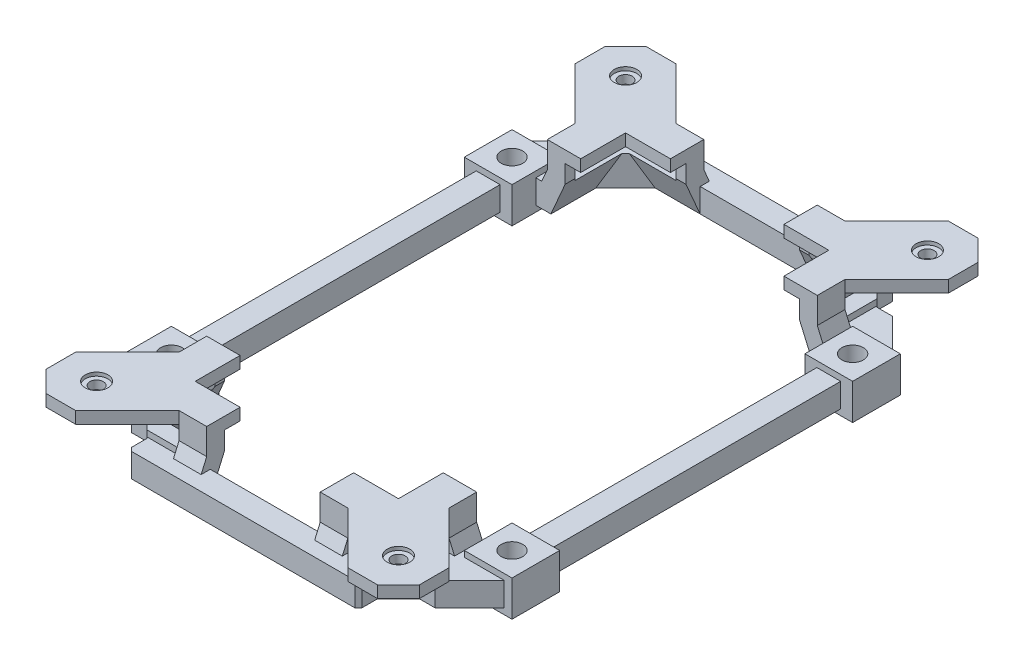
SolidWorks part; units mm, degrees
ref_plane "Front Plane" through (0, 0, 0) normal (0, 0, 1) x (1, 0, 0)
ref_plane "Top Plane" through (0, 0, 0) normal (0, 1, 0) x (1, 0, 0)
ref_plane "Right Plane" through (0, 0, 0) normal (1, 0, 0) x (0, 0, -1)
sketch "Sketch1" plane through (0, 0, 0) normal (0, 1, 0) x (1, 0, 0)
  line L0 (-53.15, 0) -> (-61.15, 0)
  line L1 (-61.15, 0) -> (-61.15, -49.15)
  line L2 (-61.15, -49.15) -> (-65.15, -49.15)
  line L3 (-65.15, -49.15) -> (-65.15, -65.15)
  line L4 (-65.15, -65.15) -> (-62.5102, -65.15)
  line L6 (-62.5102, -65.15) -> (-37.4602, -90.2)
  line L17 (-53.15, 0) -> (-53.15, -49.15)
  line L18 (-53.15, -49.15) -> (-49.15, -49.15)
  line L19 (-49.15, -49.15) -> (-49.15, -57.15)
  line L24 (-53.15, 0) -> (0, 0) construction
  line L25 (0, 0) -> (0, -92.25) construction
  line L26 (-39.3, -57.15) -> (-38.1, -57.15) construction
  line L27 (-38.1, 0) -> (-38.1, -76.2) construction
  line L28 (-65.15, -57.15) -> (-49.15, -57.15) construction
  line L29 (-38.1, -76.2) -> (0, -76.2) construction
  line L37 (-38.1, -76.2) -> (-39.3, -77.4) construction
  line L38 (-39.3, -77.4) -> (-39.3, -57.15) construction
  line L39 (-49.15, -57.15) -> (-39.3, -57.15)
  line L41 (-39.3, -77.4) -> (-19.05, -77.4) construction
  line L42 (-19.05, -77.4) -> (-19.05, -82.2)
  line L44 (-37.4602, -90.2) -> (0, -90.2)
  line L45 (0, -90.2) -> (0, -82.2)
  line L46 (0, -82.2) -> (-19.05, -82.2)
  line L47 (-39.3, -57.15) -> (-39.3, -74.6464)
  line L49 (-36.5464, -77.4) -> (-19.05, -77.4)
  line L50 (-19.05, -77.4) -> (-19.05, -76.2) construction
  line L51 (-39.3, -74.6464) -> (-36.5464, -77.4)
  line L52 (-39.3, -74.6464) -> (-49.15, -64.7964) construction
  line L53 (-49.15, -64.7964) -> (-49.15, -57.15) construction
  point P37 (-57.15, 0)
  dimension "D1" = 8
  dimension "D2" = 16
  dimension "D4" = 57.15
  dimension "D5" = 57.15
  dimension "D6" = 76.2
  dimension "D7" = 38.1
  dimension "D8" = 45
  dimension "D10" = 6
  dimension "D3" = 1.2
  dimension "D11" = 135
  dimension "D12" = 0.25
  dimension "D13" = 7.75
extrude "Boss-Extrude1" add sketch "Sketch1" along normal blind 8
sketch "Sketch2" plane through (0, 0, 0) normal (0, -1, 0) x (1, 0, 0)
  line L0 (-49.15, 57.15) -> (-49.15, 49.15) construction
  line L1 (-65.15, 49.15) -> (-65.15, 65.15) construction
  line L2 (-49.15, 57.15) -> (-49.15, 49.15)
  line L3 (-65.15, 49.15) -> (-65.15, 65.15)
  line L5 (-65.15, 49.15) -> (-49.15, 49.15)
  line L6 (-65.15, 65.15) -> (-49.15, 65.15)
  line L7 (-49.15, 65.15) -> (-49.15, 57.15)
extrude "Boss-Extrude2" add sketch "Sketch2" along normal blind 2
sketch "Sketch3" plane through (0, 8, 0) normal (0, 1, 0) x (1, 0, 0)
  line L4 (-39.3, -57.15) -> (-45.3, -57.15)
  line L6 (-45.3, -57.15) -> (-45.3, -77.1317)
  line L9 (-19.05, -83.4) -> (-19.05, -77.4)
  line L10 (-45.3, -77.1317) -> (-39.0317, -83.4)
  line L11 (-39.0317, -83.4) -> (-19.05, -83.4)
  line L12 (-62.5102, -65.15) -> (-37.4602, -90.2) construction
  line L13 (-39.3, -57.15) -> (-39.3, -74.6464)
  line L14 (-39.3, -74.6464) -> (-36.5464, -77.4)
  line L15 (-36.5464, -77.4) -> (-19.05, -77.4)
  line L16 (-19.05, -77.4) -> (-36.5464, -77.4) construction
  line L17 (-39.3, -74.6464) -> (-39.3, -57.15) construction
  line L18 (-39.3, -57.15) -> (-49.15, -57.15) construction
  line L19 (-19.05, -82.2) -> (-19.05, -77.4) construction
  line L20 (-39.3, -74.6464) -> (-43.5426, -78.8891) construction
  line L21 (-39.3, -74.6464) -> (-45.3, -74.6464) construction
  dimension "D1" = 6
extrude "Boss-Extrude3" add sketch "Sketch3" along normal blind 9.05
sketch "Sketch4" plane through (0, 17.05, 0) normal (0, 1, 0) x (1, 0, 0)
  line L0 (-45.3, -57.15) -> (-34.1, -57.15)
  line L1 (-34.1, -57.15) -> (-34.1, -72.2)
  line L2 (-34.1, -72.2) -> (-19.05, -72.2)
  line L3 (-19.05, -72.2) -> (-19.05, -83.4)
  line L4 (-19.05, -83.4) -> (-28.3294, -83.4)
  line L5 (-39.0317, -83.4) -> (-19.05, -83.4) construction
  line L6 (-28.3294, -83.4) -> (-45.6806, -100.7511)
  line L7 (-45.6806, -100.7511) -> (-55.6217, -100.7511)
  line L8 (-55.6217, -100.7511) -> (-62.6511, -93.7217)
  line L9 (-62.6511, -93.7217) -> (-62.6511, -83.7806)
  line L10 (-62.6511, -83.7806) -> (-45.3, -66.4294)
  line L11 (-45.3, -66.4294) -> (-45.3, -57.15)
  line L12 (-50.6511, -88.7511) -> (-59.1364, -97.2364) construction
  line L13 (-50.6511, -88.7511) -> (-62.6511, -88.7511) construction
  line L14 (-49.0602, -87.1602) -> (-42.1659, -80.2659) construction
  line L15 (-45.3, -77.1317) -> (-39.0317, -83.4) construction
  line L16 (-60.7274, -81.8569) -> (-43.7569, -98.8274) construction
  line L20 (-50.6511, -88.7511) -> (-42.1659, -80.2659) construction
  line L22 (-45.3, -66.4294) -> (-39.3, -60.4294) construction
  line L23 (-39.3, -74.6464) -> (-39.3, -57.15) construction
  circle A0 centre (-50.6511, -88.7511) radius 2.25
  circle A1 centre (-50.6511, -88.7511) radius 10 construction
  dimension "D4" = 4.5
  dimension "D7" = 20
  dimension "D1" = 11.2
  dimension "D2" = 135
  dimension "D3" = 135
  dimension "D5" = 12
extrude "Boss-Extrude4" add sketch "Sketch4" along normal blind 4
sketch "Sketch5" plane through (-61.2159, 0, 61.2159) normal (-0.7071, 0, 0.7071) x (0.7071, 0, 0.7071)
  line L1 (14.9408, 17.05) -> (38.9408, 17.05)
  line L2 (14.9408, 17.05) -> (14.9408, 10.05)
  line L3 (14.9408, 10.05) -> (38.9408, 10.05)
  line L4 (38.9408, 17.05) -> (38.9408, 10.05)
  line L6 (22.5084, 17.05) -> (31.3731, 17.05) construction
  line L7 (14.9408, 21.05) -> (14.9408, 17.05) construction
  line L9 (38.9408, 21.05) -> (38.9408, 17.05) construction
  dimension "D1" = 7
extrude "Cut-Extrude1" cut sketch "Sketch5" against normal up to next and the other way through all
sketch "Sketch7" plane through (0, 0, 0) normal (0, -1, 0) x (1, 0, 0)
  line L0 (-37.4602, 90.2) -> (-34.1464, 82.2) construction
  line L1 (-31.8865, 84.46) -> (-37.4059, 78.9405) construction
  line L2 (-34.1464, 82.2) -> (0, 82.2) construction
  line L3 (0, 82.2) -> (-19.05, 82.2) construction
  line L4 (-62.5102, 65.15) -> (-37.4602, 90.2) construction
  line L5 (-37.4602, 90.2) -> (0, 90.2) construction
sketch "Sketch6" plane through (-19.05, 0, 0) normal (1, 0, 0) x (0, 0, -1)
  line L1 (-82.2, 0) -> (-77.4, 11.05)
  line L2 (-77.4, 17.05) -> (-77.4, 0) construction
  line L3 (-77.4, 11.05) -> (-77.4, 0)
  line L5 (-77.4, 17.05) -> (-72.2, 17.05) construction
  line L8 (-82.2, 0) -> (-77.4, 0)
  dimension "D1" = 6
extrude "Cut-Extrude2" cut sketch "Sketch6" against normal up to vertex (15.0964 mm away) up to point (-34.1464, 0, 82.2)
ref_plane "Plane1" through (19.05, 0, 19.05) normal (0.7071, 0, 0.7071) x (0.7071, 0, -0.7071)
mirror "Mirror1" about plane through (19.05, 0, 19.05) normal (0.7071, 0, 0.7071) of "Cut-Extrude2"
sketch "Sketch8" plane through (19.05, 0, 19.05) normal (0.7071, 0, 0.7071) x (0.7071, 0, -0.7071)
  line L8 (-82.2694, 0) -> (-82.2694, 10.05)
  line L9 (-82.2694, 10.05) -> (-78.8752, 10.05)
  line L10 (-78.8752, 10.05) -> (-78.8752, 0)
  line L11 (-78.8752, 0) -> (-82.2694, 0)
  line L12 (-78.8752, 0) -> (-78.8752, 10.05) construction
  line L13 (-79.1824, 10.05) -> (-78.8752, 10.05) construction
extrude "Cut-Extrude3" cut sketch "Sketch8" against normal up to surface and the other way up to surface up to face at (-41.0448, 7.0333, 63.3477) other way up to face at (-25.2477, 7.0333, 79.1448)
sketch "Sketch10" plane through (-19.05, 0, 0) normal (1, 0, 0) x (0, 0, -1)
  line L0 (-83.4, 12.2969) -> (-85.2665, 8)
  line L1 (-85.2665, 8) -> (-83.4, 8)
  line L2 (-83.4, 8) -> (-83.4, 12.2969)
  line L3 (-83.4, 21.05) -> (-83.4, 8) construction
  line L4 (-90.2, 8) -> (-82.2, 8) construction
  line L5 (-77.4, 11.05) -> (-82.2, 0) construction
  line L6 (-77.8344, 10.05) -> (-82.2, 0) construction
  dimension "D1" = 6
extrude "Boss-Extrude5" add sketch "Sketch10" against normal up to vertex (9.2794 mm away) up to point (-28.3294, 10.05, 83.4)
sketch "Sketch11" plane through (19.05, 0, 19.05) normal (0.7071, 0, 0.7071) x (0.7071, 0, -0.7071)
  line L0 (-86.5723, -12.3407) -> (-80.3245, 8)
  line L1 (-80.3245, 8) -> (-86.5723, 8)
  line L2 (-86.5723, 8) -> (-86.5723, -12.3407)
  line L3 (-86.5723, 10.05) -> (-86.5723, 8) construction
  line L4 (-80.3245, 8) -> (-79.0046, 8) construction
  line L5 (-79.0046, 12.2969) -> (-80.3245, 8) construction
extrude "Cut-Extrude4" [suppressed] cut sketch "Sketch11" along normal through all
mirror "Mirror2" about plane through (19.05, 0, 19.05) normal (0.7071, 0, 0.7071) of "Cut-Extrude4", "Boss-Extrude5"
sketch "Sketch12" plane through (0, 8, 0) normal (0, 1, 0) x (1, 0, 0)
  line L0 (-65.15, -65.15) -> (-49.15, -49.15) construction
  circle A0 centre (-57.15, -57.15) radius 3.6
  point P7 (-57.15, -57.15)
  dimension "D1" = 7.2
extrude "Cut-Extrude5" cut sketch "Sketch12" against normal through all
mirror "Mirror3" about plane through (-53.15, 8, 0) normal (0, 0, 1) of bodies 112
mirror "Mirror4" about plane through (0, 8, -90.2) normal (-1, 0, 0) of bodies 113
sketch "Sketch13" plane through (0, 8, 0) normal (0, 1, 0) x (1, 0, 0)
  line L0 (-49.15, 49.15) -> (-53.15, 49.15) construction
  line L1 (-65.15, 65.15) -> (-49.15, 65.15)
  line L2 (-65.15, 65.15) -> (-65.15, 49.15)
  line L3 (-65.15, 49.15) -> (-49.15, 49.15)
  line L4 (-49.15, 65.15) -> (-49.15, 49.15)
  line L5 (-65.15, -49.15) -> (-49.15, -49.15)
  line L6 (-65.15, -49.15) -> (-65.15, -65.15)
  line L7 (-65.15, -65.15) -> (-49.15, -65.15)
  line L8 (-49.15, -49.15) -> (-49.15, -65.15)
  line L9 (49.15, -49.15) -> (65.15, -49.15)
  line L10 (49.15, -49.15) -> (49.15, -65.15)
  line L11 (49.15, -65.15) -> (65.15, -65.15)
  line L12 (65.15, -49.15) -> (65.15, -65.15)
  line L13 (49.15, 65.15) -> (65.15, 65.15)
  line L14 (49.15, 65.15) -> (49.15, 49.15)
  line L15 (49.15, 49.15) -> (65.15, 49.15)
  line L16 (65.15, 65.15) -> (65.15, 49.15)
  line L17 (-49.15, 57.15) -> (-49.15, 49.15) construction
  line L18 (-65.15, -65.15) -> (-62.5102, -65.15) construction
  line L19 (-65.15, -49.15) -> (-65.15, -65.15) construction
  line L20 (-49.15, -57.15) -> (-49.15, -49.15) construction
  line L21 (-49.15, -49.15) -> (-53.15, -49.15) construction
  line L22 (65.15, -65.15) -> (62.5102, -65.15) construction
  line L23 (61.15, -49.15) -> (65.15, -49.15) construction
  line L24 (65.15, -49.15) -> (65.15, -65.15) construction
  line L25 (49.15, -57.15) -> (49.15, -49.15) construction
  line L26 (65.15, 65.15) -> (62.5102, 65.15) construction
  line L27 (61.15, 49.15) -> (65.15, 49.15) construction
  line L28 (49.15, 57.15) -> (49.15, 49.15) construction
  line L29 (65.15, 49.15) -> (65.15, 65.15) construction
  line L30 (-65.15, 49.15) -> (-65.15, 65.15) construction
  line L31 (-65.15, 65.15) -> (-62.5102, 65.15) construction
  circle A0 centre (57.15, 57.15) radius 3.6 construction
  circle A1 centre (57.15, -57.15) radius 3.6 construction
  circle A2 centre (-57.15, -57.15) radius 3.6 construction
  circle A3 centre (-57.15, 57.15) radius 3.6 construction
  circle A4 centre (57.15, 57.15) radius 3.6
  circle A5 centre (57.15, -57.15) radius 3.6
  circle A6 centre (-57.15, -57.15) radius 3.6
  circle A7 centre (-57.15, 57.15) radius 3.6
extrude "Boss-Extrude6" add sketch "Sketch13" along normal blind 2
sketch "Sketch15" [suppressed] plane through (0, 0, 77.4) normal (0, 0, -1) x (-1, 0, 0)
  line L0 (39.3, 17.05) -> (-39.3, 17.05) construction
  line L1 (-37.4285, 0) -> (39.3, 17.05) construction
  line L2 (-37.5, 17.05) -> (-10.1111, 17.05)
  line L3 (-10.1111, 17.05) -> (-10.1111, 6.0703)
  line L4 (44.1, 0) -> (34.1464, 0) construction
  line L5 (-10.1111, 6.0703) -> (-35.6713, 0.3905)
  arc A0 (-39.3, 17.05) -> (-37.4285, 0) centre (39.3, 17.05) ccw construction
  arc A1 (-37.5, 17.05) -> (-35.6713, 0.3905) centre (39.3, 17.05) ccw
  dimension "D1" = 76.8
ref_plane "Plane2" [suppressed] through (39.1232, 9.05, 77.2232) normal (-0.7071, 0, 0.7071) x (0.7071, 0, 0.7071)
sketch "Sketch16" [suppressed] plane through (39.1232, 9.05, 77.2232) normal (-0.7071, 0, 0.7071) x (0.7071, 0, 0.7071)
  line L0 (-0.0384, 0.0028) -> (0, 0)
  line L1 (0.4004, 6.0709) -> (-0.1484, -1.5179) construction
  line L2 (0, 0) -> (-0.036, 0.036)
  line L3 (0, 0) -> (-2.9537, 0) construction
  ellipse E0 centre (-55.3286, 8) end of major axis (-55.3286, 86.6) minor radius 55.5786 (-1.0734, -9.05) -> (0.25, 8) ccw construction
  dimension "D1" = 45
sketch "Sketch17" [suppressed] plane through (-39.3, 0, 0) normal (1, 0, 0) x (0, 0, -1)
  line L0 (77.4, 17.05) -> (-77.4, 17.05) construction
  line L1 (-77.4, 17.05) -> (76.4582, 0) construction
  line L2 (-77.4, 17.05) -> (-77.4, 11.05) construction
  line L3 (77.4, 17.05) -> (77.4, 11.05) construction
  line L4 (72.2464, 0) -> (82.2, 0) construction
  line L5 (-72.2, 17.05) -> (-58.2, 17.05) construction
  line L6 (76.2, 17.05) -> (27.7638, 17.05)
  line L7 (27.7638, 17.05) -> (27.7638, 5.3961)
  line L8 (27.7638, 5.3961) -> (75.2655, 0.1322)
  arc A0 (77.4, 17.05) -> (76.4582, 0) centre (-77.4, 17.05) cw construction
  arc A1 (76.2, 17.05) -> (75.2655, 0.1322) centre (-77.4, 17.05) cw
  dimension "D1" = 153.6
sketch "Sketch19" plane through (0, 0, 0) normal (0, -1, 0) x (1, 0, 0)
  line L0 (38.6511, 83.7806) -> (45.6806, 76.7511)
  line L1 (45.6806, 76.7511) -> (55.6217, 76.7511)
  line L2 (55.6217, 76.7511) -> (50.6511, 71.7806) construction
  line L4 (33.6806, 88.7511) -> (38.6511, 93.7217) construction
  line L5 (38.6511, 93.7217) -> (38.6511, 83.7806)
  line L6 (45.3, 66.4294) -> (62.6511, 83.7806) construction
  line L7 (45.6806, 100.7511) -> (28.3294, 83.4) construction
  line L8 (55.6217, 100.7511) -> (45.6806, 100.7511) construction
  line L9 (50.6511, 88.7511) -> (59.1364, 97.2364) construction
  line L10 (62.6511, 93.7217) -> (55.6217, 100.7511) construction
  line L12 (50.6511, 71.7806) -> (45.6806, 76.7511) construction
  line L13 (33.6806, 88.7511) -> (38.6511, 83.7806) construction
  line L14 (42.1659, 80.2659) -> (50.6511, 88.7511) construction
  line L15 (38.6511, 93.7217) -> (55.6217, 76.7511)
  circle A0 centre (50.6511, 88.7511) radius 2.25 construction
  dimension "D1" = 135
extrude "Cut-Extrude6" cut sketch "Sketch19" against normal up to vertex (8 mm away)
mirror "Mirror5" about plane through (0, 0, 0) normal (1, 0, 0) of "Cut-Extrude6" second plane through (0, 0, 0) second plane normal (0, 0, 1)
sketch "Sketch20" plane through (0, 21.05, 0) normal (0, 1, 0) x (1, 0, 0)
  circle A0 centre (-50.6511, 88.7511) radius 3.8
  dimension "D1" = 7.6
extrude "Cut-Extrude7" cut sketch "Sketch20" against normal blind 1.2
mirror "Mirror6" about plane through (0, 0, 0) normal (0, 0, 1) of "Cut-Extrude7" second plane through (0, 0, 0) second plane normal (1, 0, 0)
equation "\"sample_clearance\"= 1.2'sample to edge wall"
equation "\"truss_width\"= 8'f"
equation "\"truss_height\"= 8'thickness"
equation "\"truss_offset\"= 2'height offset from baseplate"
equation "\"D1@Sketch1\"=\"truss_width\""
equation "\"screw_spacing_short\"= 4.5in'baseplate spacing parallel to sample short side"
equation "\"screw_spacing_long\"= 4.5in'baseplate spacing parallel to sample long side"
equation "\"truss_bore_width\"= 16'box around bore hole"
equation "\"D2@Sketch1\"=\"truss_bore_width\""
equation "\"D4@Sketch1\"=\"screw_spacing_long\"/2"
equation "\"D5@Sketch1\"=\"screw_spacing_short\"/2"
equation "\"sample_long\"= 6in"
equation "\"sample_short\"= 3in"
equation "\"D6@Sketch1\"=\"sample_long\"/2"
equation "\"D7@Sketch1\"=\"sample_short\"/2"
equation "\"base_clearance_corner\"= 2"
equation "\"wall\"= 12"
equation "\"sample_short_to_truss\"= 6"
equation "\"D10@Sketch1\"=\"sample_short_to_truss\""
equation "\"D1@Boss-Extrude1\"=\"truss_height\""
equation "\"D1@Boss-Extrude2\"=\"truss_offset\""
equation "\"D1@Boss-Extrude3\"=0.75in - \"truss_offset\" - \"truss_height\""
equation "\"D3@Sketch1\"=\"sample_clearance\""
equation "\"D1@Sketch4\"=\"sample_clearance\"+10"
equation "\"D1@Boss-Extrude6\"=12-\"truss_offset\"-\"truss_height\""
equation "\"D12@Sketch1\"=\"truss_width\"-7.75"
equation "\"D7@Sketch4\"=19+1"
equation "\"D1@Sketch20\"=6.6+1"
